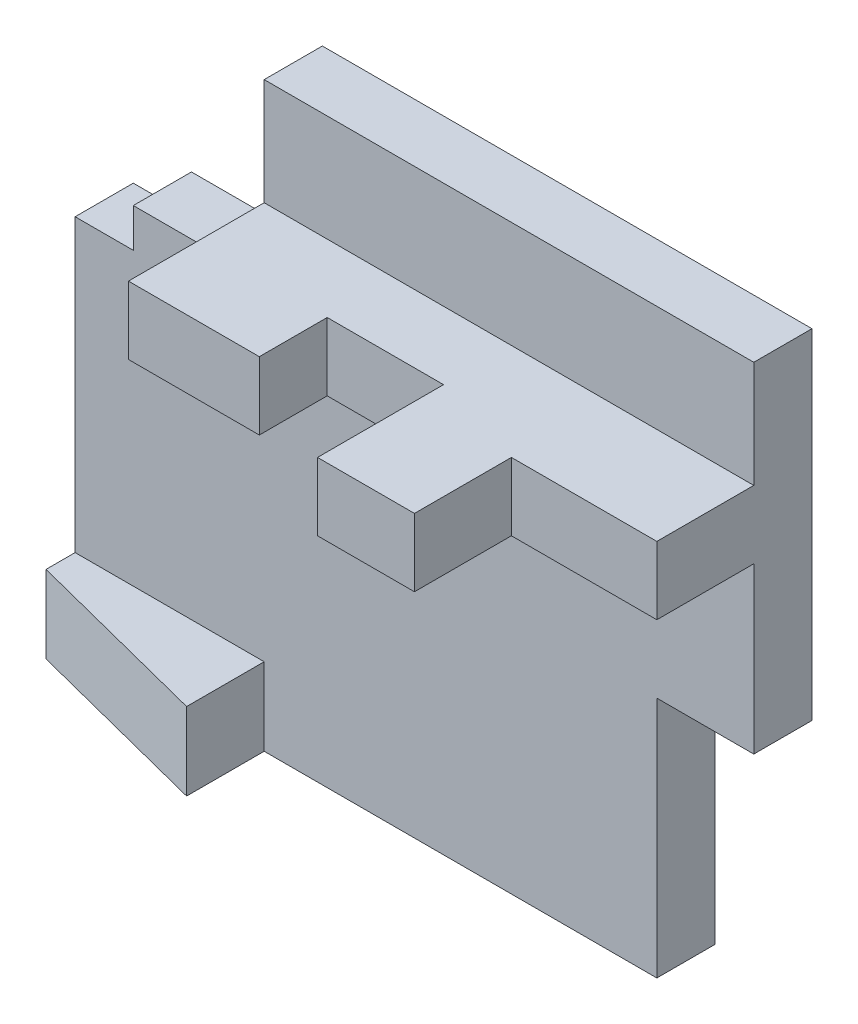
SolidWorks part; units mm, degrees
ref_plane "Спереди" through (0, 0, 0) normal (0, 0, 1) x (1, 0, 0)
ref_plane "Сверху" through (0, 0, 0) normal (0, 1, 0) x (1, 0, 0)
ref_plane "Справа" through (0, 0, 0) normal (1, 0, 0) x (0, 0, -1)
sketch "Эскиз1" plane through (0, 0, 0) normal (0, 0, 1) x (1, 0, 0)
  line L1 (-35, -30) -> (35, -30)
  line L2 (-35, -30) -> (-35, 30)
  line L3 (-35, 30) -> (35, 30)
  line L4 (35, -30) -> (35, 30)
  line L5 (-35, -30) -> (35, 30) construction
  line L6 (-35, 30) -> (35, -30) construction
  line L7 (-33.5, 12) -> (-15.5, 12)
  line L8 (-33.5, 12) -> (-33.5, 30)
  line L9 (-33.5, 30) -> (-15.5, 30)
  line L10 (-15.5, 12) -> (-15.5, 30)
  line L11 (-33.5, 12) -> (-15.5, 30) construction
  line L12 (-33.5, 30) -> (-15.5, 12) construction
  line L13 (-29, 8) -> (-35, 8)
  line L14 (-29, 8) -> (-29, 12)
  line L15 (-29, 12) -> (-35, 12)
  line L16 (-35, 8) -> (-35, 12)
  line L17 (-29, 8) -> (-35, 12) construction
  line L18 (-29, 12) -> (-35, 8) construction
  line L19 (35, -30) -> (25, -30)
  line L20 (35, -30) -> (35, -5)
  line L21 (35, -5) -> (25, -5)
  line L22 (25, -30) -> (25, -5)
  point P0 (0, 0)
  point P6 (-24.5, 21)
  point P11 (-32, 10)
  dimension "D1" = 70
  dimension "D2" = 60
  dimension "D3" = 18
  dimension "D4" = 4
  dimension "D5" = 6
  dimension "D6" = 10
  dimension "D7" = 25
extrude "Бобышка-Вытянуть1" add sketch "Эскиз1" along normal blind 6 contours L1 L22 L21 L4 L3 L10 L7 L14 L13 L2
sketch "Эскиз2" plane through (0, -30, 0) normal (0, -1, 0) x (1, 0, 0)
  line L0 (-35, 6) -> (-35, 9)
  line L1 (-35, 9) -> (-15.5, 14)
  line L2 (-15.5, 14) -> (-15.5, 6)
  line L3 (-35, 6) -> (25, 6) construction
  line L4 (-15.5, 6) -> (-35, 6)
  line L5 (-15.5, 6) -> (-15.5, 0) construction
  dimension "D1" = 8
  dimension "D3" = 3
extrude "Бобышка-Вытянуть3" add sketch "Эскиз2" against normal blind 8
sketch "Эскиз3" plane through (-35, 0, 0) normal (-1, 0, 0) x (0, 0, 1)
  line L0 (0, -30) -> (0, 8) construction
  line L1 (0, -13) -> (3, -13)
  line L2 (0, -13) -> (0, 1)
  line L3 (0, 1) -> (3, 1)
  line L4 (3, -13) -> (3, 1)
  line L5 (9, -30) -> (0, -30) construction
  dimension "D1" = 14
  dimension "D2" = 3
  dimension "D3" = 17
extrude "Вырез-Вытянуть1" cut sketch "Эскиз3" against normal blind 47
sketch "Эскиз4" plane through (0, 0, 6) normal (0, 0, 1) x (1, 0, 0)
  line L0 (35, -5) -> (35, 30) construction
  line L1 (35, 19) -> (-15.5, 19)
  line L2 (35, 19) -> (35, 12)
  line L3 (35, 12) -> (-15.5, 12)
  line L4 (-15.5, 19) -> (-15.5, 12)
  line L5 (-29, 12) -> (-15.5, 12) construction
  line L7 (-15.5, 12) -> (-15.5, 30) construction
  dimension "D2" = 7
extrude "Бобышка-Вытянуть4" add sketch "Эскиз4" along normal blind 20
sketch "Эскиз5" plane through (0, 19, 0) normal (0, 1, 0) x (1, 0, 0)
  line L0 (35, -26) -> (-15.5, -26) construction
  line L1 (35, -26) -> (20, -26)
  line L2 (35, -26) -> (35, -16)
  line L3 (35, -16) -> (20, -16)
  line L4 (20, -26) -> (20, -16)
  line L5 (10, -26) -> (-2, -26)
  line L6 (10, -26) -> (10, -13)
  line L7 (10, -13) -> (-2, -13)
  line L8 (-2, -26) -> (-2, -13)
  line L10 (-15.5, -26) -> (-2, -26)
  line L11 (-15.5, -26) -> (-15.5, -20)
  line L12 (-15.5, -20) -> (-2, -20)
  line L13 (-2, -26) -> (-2, -20)
  line M2 (-15.5, -6) -> (-15.5, -26)
  line M3 (-15.5, -26) -> (35, -26)
  dimension "D1" = 10
  dimension "D2" = 15
  dimension "D3" = 10
  dimension "D4" = 12
  dimension "D5" = 13
  dimension "D6" = 6
extrude "Вырез-Вытянуть2" cut sketch "Эскиз5" against normal up to next contours L8 L6 L7 M3 | L12 L8 M2 M3 | L4 L3 L2 L1
